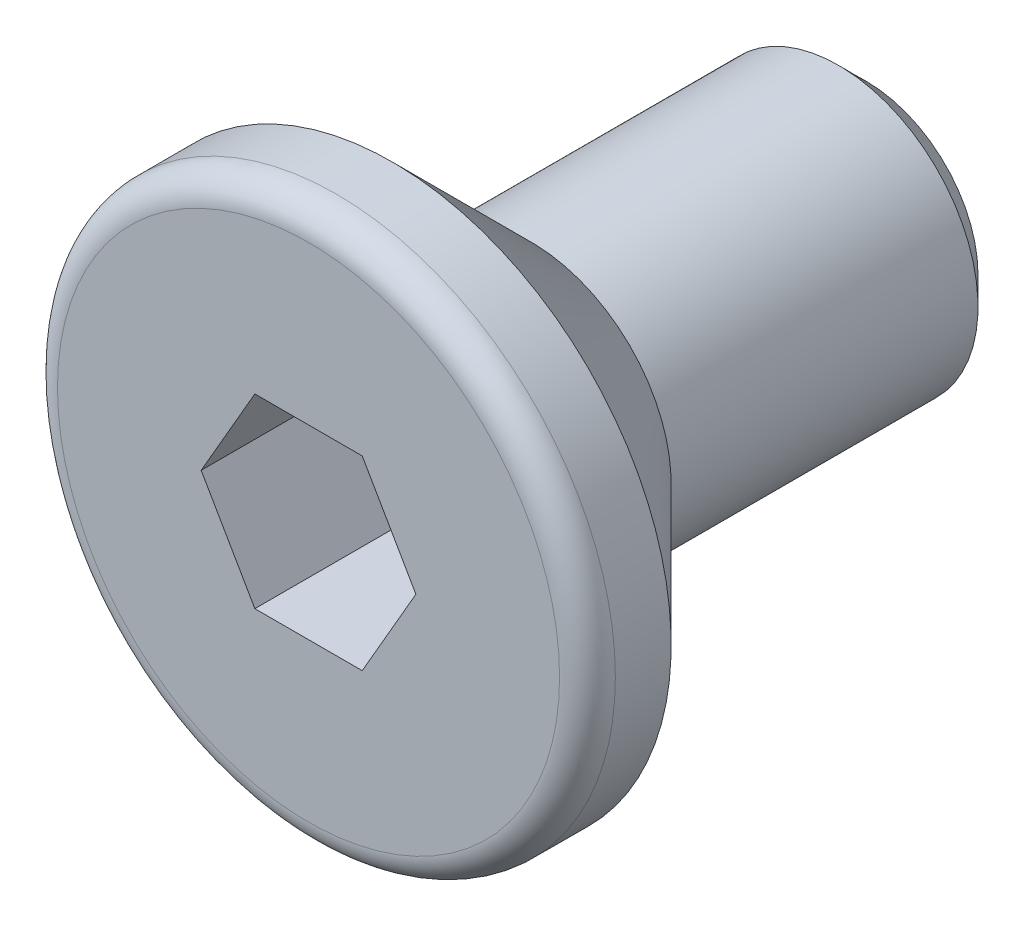
SolidWorks part; units mm, degrees
ref_plane "前视基准面" through (0, 0, 0) normal (0, 0, 1) x (1, 0, 0)
ref_plane "上视基准面" through (0, 0, 0) normal (0, 1, 0) x (1, 0, 0)
ref_plane "右视基准面" through (0, 0, 0) normal (1, 0, 0) x (0, 0, -1)
sketch "草图1" plane through (0, 0, 0) normal (1, 0, 0) x (0, 0, -1)
  line L0 (-3, 0) -> (-3, 3)
  line L1 (-3, 3) -> (-2.1, 3)
  line L2 (-2.1, 3) -> (-0.6, 1.5)
  line L3 (-0.6, 1.5) -> (2.7, 1.5)
  line L4 (2.7, 1.5) -> (3, 1.2)
  line L5 (3, 1.2) -> (3, 0)
  line L6 (3, 0) -> (-3, 0)
  dimension "D1" = 6
  dimension "D2" = 3
  dimension "D3" = 45
  dimension "D4" = 0.3
  dimension "D5" = 2.4
  dimension "D6" = 1.5
revolve "旋转1" add sketch "草图1" angle 360 about L6
sketch "草图2" plane through (0, 0, 3) normal (0, 0, 1) x (1, 0, 0)
  line L1 (1.1547, 0) -> (0.5774, 1)
  line L2 (0.5774, 1) -> (-0.5774, 1)
  line L3 (-0.5774, 1) -> (-1.1547, 0)
  line L4 (-1.1547, 0) -> (-0.5774, -1)
  line L5 (-0.5774, -1) -> (0.5774, -1)
  line L6 (0.5774, -1) -> (1.1547, 0)
  circle A0 centre (0, 0) radius 1 construction
  dimension "D1" = 2
extrude "切除-拉伸1" cut sketch "草图2" against normal blind 1.5
fillet "圆角1" radius 0.3 1 edges at (-3, 0, 3)
